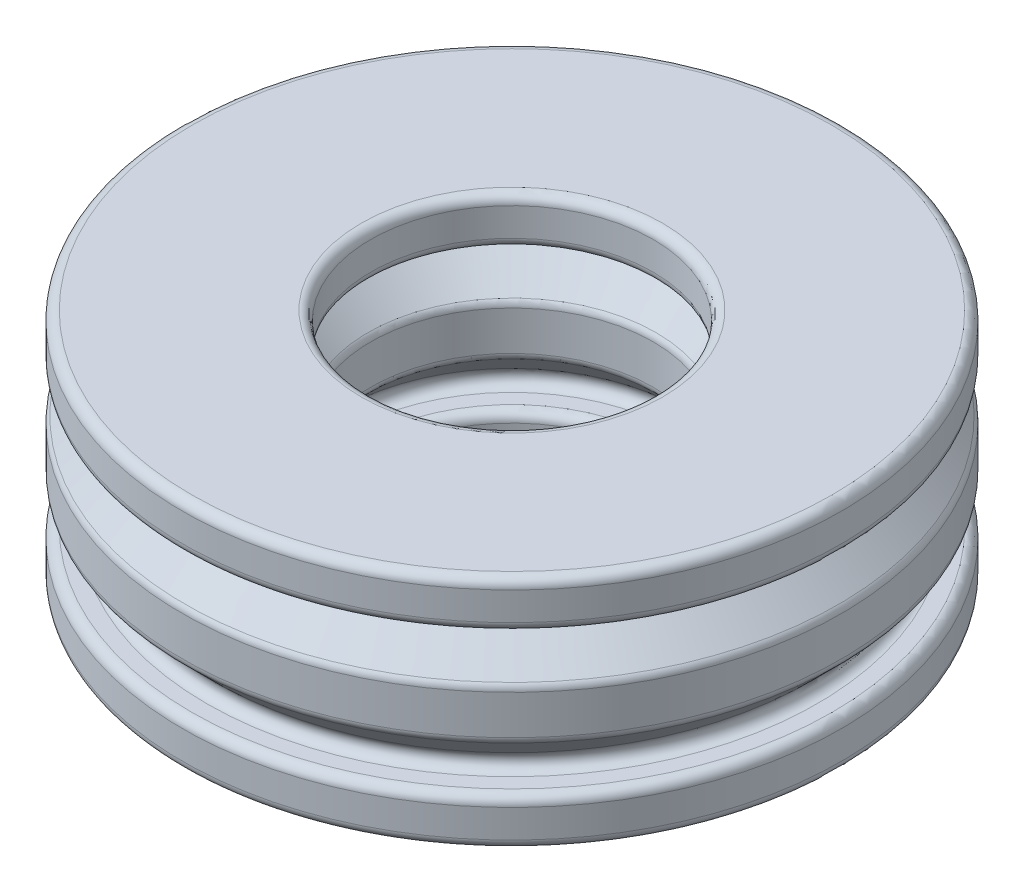
SolidWorks part; units mm, degrees
material "AISI 304"
ref_plane "前视基准面" through (0, 0, 0) normal (0, 0, 1) x (1, 0, 0)
ref_plane "上视基准面" through (0, 0, 0) normal (0, 1, 0) x (1, 0, 0)
ref_plane "右视基准面" through (0, 0, 0) normal (1, 0, 0) x (0, 0, -1)
sketch "草图1" plane through (0, 0, 0) normal (0, 0, 1) x (1, 0, 0)
  line L0 (0, 0) -> (0, 5) construction
  line L1 (-3, 0.2) -> (-3, 0.8)
  line L2 (-3.2, 5) -> (-6.8, 5)
  line L3 (-7, 4.8) -> (-7, 4.2)
  line L4 (-6.8, 0) -> (-3.2, 0)
  line L5 (-6.8, 4) -> (-6.4828, 4)
  line L6 (-6.3414, 3.6586) -> (-6.9414, 3.0586)
  line L7 (-6.9414, 1.9414) -> (-6.3414, 1.3414)
  line L8 (-6.4828, 1) -> (-6.8, 1)
  line L9 (-3.2, 4) -> (-3.5172, 4)
  line L10 (-3.6586, 3.6586) -> (-3.0586, 3.0586)
  line L11 (-3.2, 1) -> (-3.5172, 1)
  line L12 (-3.6586, 1.3414) -> (-3.0586, 1.9414)
  line L13 (-7, 2.9172) -> (-7, 2.0828)
  line L14 (-7, 0.8) -> (-7, 0.2)
  line L15 (-3, 4.2) -> (-3, 4.8)
  line L16 (-3, 2.0828) -> (-3, 2.9172)
  arc A0 (-3.0586, 1.9414) -> (-3, 2.0828) centre (-3.2, 2.0828) ccw
  arc A1 (-3.5172, 1) -> (-3.6586, 1.3414) centre (-3.5172, 1.2) cw
  arc A2 (-3.2, 1) -> (-3, 0.8) centre (-3.2, 0.8) cw
  arc A3 (-3.0586, 3.0586) -> (-3, 2.9172) centre (-3.2, 2.9172) cw
  arc A4 (-3.5172, 4) -> (-3.6586, 3.6586) centre (-3.5172, 3.8) ccw
  arc A5 (-6.8, 1) -> (-7, 0.8) centre (-6.8, 0.8) ccw
  arc A6 (-3.2, 4) -> (-3, 4.2) centre (-3.2, 4.2) ccw
  arc A7 (-6.3414, 1.3414) -> (-6.4828, 1) centre (-6.4828, 1.2) cw
  arc A8 (-6.9414, 3.0586) -> (-7, 2.9172) centre (-6.8, 2.9172) ccw
  arc A9 (-6.9414, 1.9414) -> (-7, 2.0828) centre (-6.8, 2.0828) cw
  arc A10 (-6.4828, 4) -> (-6.3414, 3.6586) centre (-6.4828, 3.8) cw
  arc A11 (-7, 0.2) -> (-6.8, 0) centre (-6.8, 0.2) ccw
  arc A12 (-6.8, 4) -> (-7, 4.2) centre (-6.8, 4.2) cw
  arc A13 (-6.8, 5) -> (-7, 4.8) centre (-6.8, 4.8) ccw
  arc A14 (-3, 4.8) -> (-3.2, 5) centre (-3.2, 4.8) ccw
  arc A15 (-3, 0.2) -> (-3.2, 0) centre (-3.2, 0.2) cw
  point P22 (-3, 2)
  point P33 (-7, 1)
  point P36 (-3, 4)
  point P39 (-6, 1)
  point P42 (-7, 3)
  point P45 (-7, 2)
  point P48 (-6, 4)
  point P51 (-7, 0)
  point P54 (-7, 4)
  point P57 (-7, 5)
  dimension "D8" = 0.2
  dimension "D1" = 5
  dimension "D2" = 6
  dimension "D3" = 14
  dimension "D4" = 1
  dimension "D5" = 1
  dimension "D6" = 1
  dimension "D7" = 45
revolve "旋转1" add sketch "草图1" angle 360 about L0
